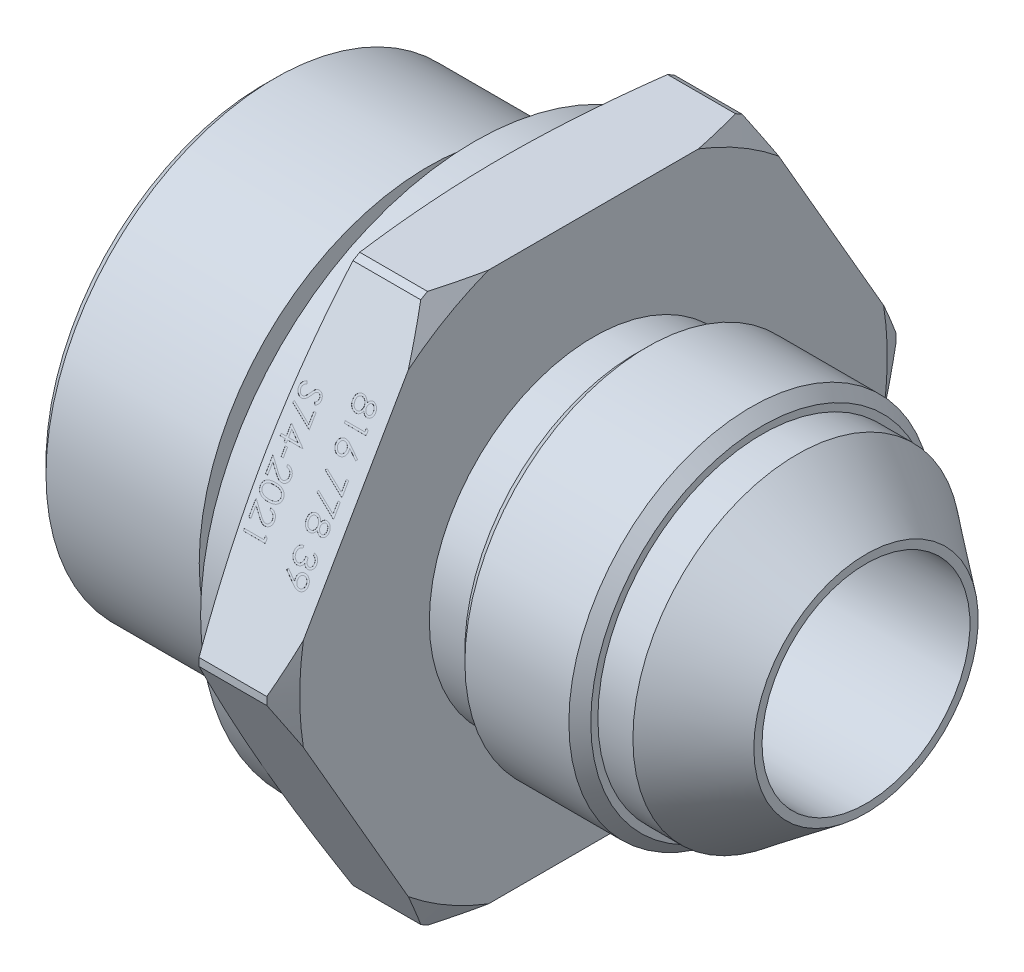
SolidWorks part; units mm, degrees
ref_plane "Front Plane" through (0, 0, 0) normal (0, 0, 1) x (1, 0, 0)
ref_plane "Top Plane" through (0, 0, 0) normal (0, 1, 0) x (1, 0, 0)
ref_plane "Right Plane" through (0, 0, 0) normal (1, 0, 0) x (0, 0, -1)
sketch "Sketch1" plane through (0, 0, 0) normal (0, 0, 1) x (1, 0, 0)
  line L0 (0, 0) -> (53.9967, 0) construction
  line L1 (0, 18.4) -> (0, 20.925)
  line L2 (15, 20.925) -> (15, 19.0336)
  line L3 (0, 20.925) -> (15, 20.925)
  line L4 (55, 9.5) -> (12.8047, 9.5)
  line L5 (22.8048, 28.75) -> (29, 28.75)
  line L6 (30.1, 26.8447) -> (30.1, 15)
  line L7 (30.1, 15) -> (34, 15)
  line L8 (34, 15) -> (34, 16.65)
  line L9 (34, 16.65) -> (45.5, 16.65)
  line L10 (45.5, 16.65) -> (45.5, 15)
  line L11 (45.5, 15) -> (48.7, 15)
  line L12 (48.7, 15) -> (55, 10.2526)
  line L13 (55, 10.2526) -> (55, 9.5)
  line L15 (21.8, 25) -> (19.2, 25)
  line L16 (19.2, 25) -> (19.2, 19.0336)
  line L18 (0, 18.4) -> (4.512, 15)
  line L19 (15, 19.0336) -> (19.2, 19.0336)
  line L20 (22.8048, 28.75) -> (21.8, 25)
  line L21 (29, 28.75) -> (30.1, 26.8447)
  line L22 (4.512, 15) -> (9.5, 15)
  line L23 (9.5, 15) -> (12.8047, 9.5)
  dimension "D3" = 30
  dimension "D4" = 6.3
  dimension "D5" = 9.5
  dimension "D6" = 33.3
  dimension "D7" = 21
  dimension "D8" = 10.9
  dimension "D9" = 8.3
  dimension "D10" = 55
  dimension "D11" = 41.85
  dimension "D12" = 15
  dimension "D13" = 57.5
  dimension "D14" = 19.2
  dimension "D15" = 50
  dimension "D16" = 1.1
  dimension "D17" = 30
  dimension "D18" = 75
  dimension "D19" = 37
  dimension "D20" = 19
  dimension "D21" = 38.0672
  dimension "D23" = 36.8
  dimension "D24" = 37
  dimension "D25" = 30
  dimension "D26" = 59
  dimension "D27" = 9.5
revolve "Revolve1" add sketch "Sketch1" angle 360 about L0
cosmetic thread "Cosmetic Thread1" parameters "D2"=39
cosmetic thread "Cosmetic Thread2" parameters "D2"=30
sketch "Sketch2" plane through (30.1, 0, 0) normal (1, 0, 0) x (0, 0, -1)
  line L1 (14.4771, 25.075) -> (-14.4771, 25.075)
  line L2 (-14.4771, 25.075) -> (-28.9541, 0)
  line L3 (-28.9541, 0) -> (-14.4771, -25.075)
  line L4 (-14.4771, -25.075) -> (14.4771, -25.075)
  line L5 (14.4771, -25.075) -> (28.9541, 0)
  line L6 (28.9541, 0) -> (14.4771, 25.075)
  circle A0 centre (0, 0) radius 25.075 construction
  dimension "D1" = 50.15
extrude "Extrude1" cut sketch "Sketch2" against normal up to surface (10.9 mm away) flip side to cut up to face at (19.2, 0, 19.0336)
chamfer "Chamfer1" distance 1 angle 45 1 edges at (0, 0, 20.925)
chamfer "Chamfer2" distance 1 angle 45 2 edges at (45.5, 0, 16.65) (34, 0, 16.65)
sketch "Sketch3" plane through (0, 12.5375, 21.7156) normal (0, 0.5, 0.866) x (1, 0, 0)
  line L0 (26.858, 12.3078) -> (26.858, -12.6117) construction
  line L1 (30.1, -15) -> (30.1, 15) construction
  text T0 "816 778 39\r\nS74-2021" font "Century Gothic" height 2
  dimension "D1" = 3.242
extrude "Cut-Extrude1" cut sketch "Sketch3" against normal blind 0.01
